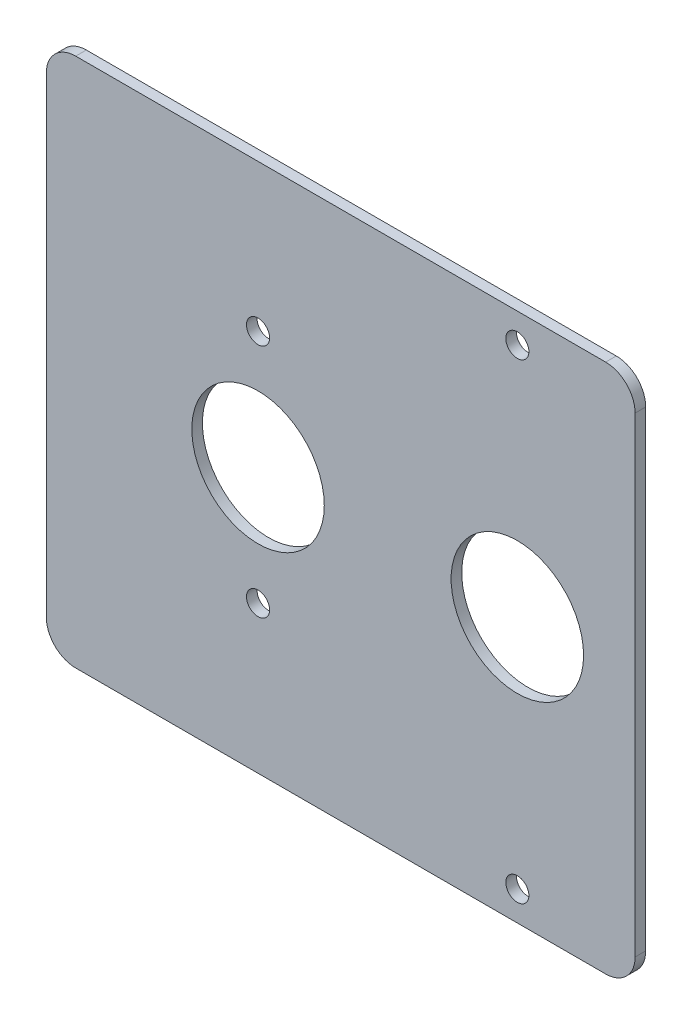
SolidWorks part; units mm, degrees
ref_plane "Front Plane" through (0, 0, 0) normal (0, 0, 1) x (1, 0, 0)
ref_plane "Top Plane" through (0, 0, 0) normal (0, 1, 0) x (1, 0, 0)
ref_plane "Right Plane" through (0, 0, 0) normal (1, 0, 0) x (0, 0, -1)
sketch "Sketch1" plane through (0, 0, 0) normal (0, 0, 1) x (1, 0, 0)
  line L1 (0, 0) -> (127, 0)
  line L2 (0, 0) -> (0, 114.3)
  line L3 (0, 114.3) -> (127, 114.3)
  line L4 (127, 0) -> (127, 114.3)
  circle A0 centre (45.6692, 82.55) radius 2.4892
  circle A1 centre (45.6692, 57.15) radius 14.2875
  circle A2 centre (45.6692, 31.75) radius 2.4892
  circle A3 centre (101.6, 107.95) radius 2.4892
  circle A4 centre (101.6, 57.15) radius 14.2875
  circle A5 centre (101.6, 6.35) radius 2.4892
  dimension "D3" = 25.4
  dimension "D10" = 25.4
  dimension "D12" = 4.9784
  dimension "D13" = 4.9784
  dimension "D14" = 28.575
  dimension "D15" = 28.575
  dimension "D16" = 4.9784
  dimension "D17" = 4.9784
  dimension "D2" = 127
  dimension "D4" = 57.15
  dimension "D5" = 50.8
  dimension "D6" = 50.8
  dimension "D7" = 6.35
  dimension "D8" = 25.4
  dimension "D9" = 25.4
  dimension "D11" = 114.3
  dimension "D18" = 55.9308
extrude "Boss-Extrude1" add sketch "Sketch1" along normal mid plane 2.286
fillet "Fillet1" radius 6.35 4 edges at (127, 114.3, 0) (127, 0, 0) (0, 0, 0) (0, 114.3, 0)
